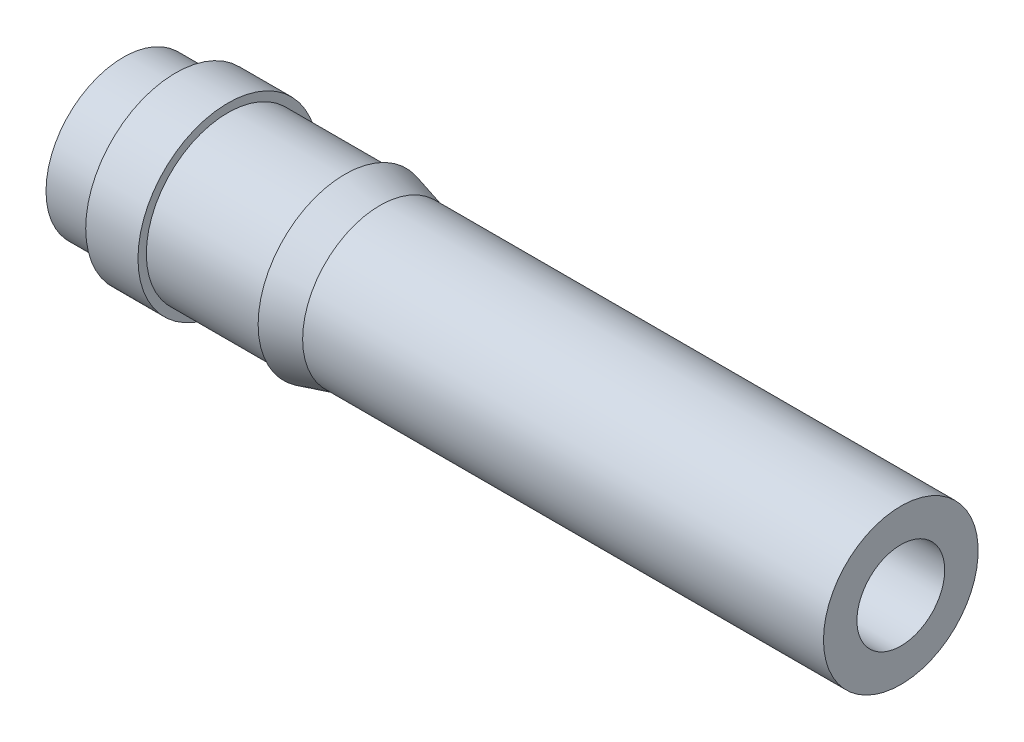
SolidWorks part; units mm, degrees
material "Brass Alloy 385"
ref_plane "Front Plane" through (0, 0, 0) normal (0, 0, 1) x (1, 0, 0)
ref_plane "Top Plane" through (0, 0, 0) normal (0, 1, 0) x (1, 0, 0)
ref_plane "Right Plane" through (0, 0, 0) normal (1, 0, 0) x (0, 0, -1)
sketch "Sketch1" plane through (0, 0, 0) normal (0, 0, 1) x (1, 0, 0)
  line L0 (0, 0) -> (0, 0.4699)
  line L1 (0.3175, 0.5461) -> (0.635, 0.5461)
  line L2 (0.635, 0.5461) -> (0.635, 0.4953)
  line L3 (0.635, 0.4953) -> (1.3462, 0.4953)
  line L4 (1.3462, 0.4953) -> (1.3462, 0.527)
  line L5 (1.3462, 0.527) -> (1.5595, 0.4699)
  line L6 (1.5595, 0.4699) -> (4.7244, 0.4699)
  line L7 (0.3175, 0.5461) -> (0.3175, 0.4699)
  line L8 (4.7244, 0.4699) -> (4.7244, 0)
  line L9 (0, 0) -> (4.7244, 0)
  line L10 (0, 0) -> (4.7244, 0) construction
  line L11 (0.3175, 0.4699) -> (0, 0.4699)
  line L12 (0, 0) -> (4.7244, 0) construction
revolve "RevolutionAngle1" add sketch "Sketch1" angle 360 about L10
hole_wizard "Hole1" positions "Sketch3" profile "Sketch2" legacy
sketch "Sketch3" plane through (0, 0, 0) normal (-1, 0, 0) x (0, 0, 1)
  point P0 (0, 0)
sketch "Sketch2" plane through (0, 0, 0) normal (0, 1, 0) x (0, 0, 1)
  line L0 (0, 0) -> (0, 4.1476)
  line L1 (0, 4.1476) -> (0.3505, 3.937)
  line L2 (0.3505, 3.937) -> (0.3505, 0)
  line L4 (0.3505, 0) -> (0, 0)
  line L6 (0, 4.1476) -> (-0.3505, 3.937) construction
  line L7 (0, -4.2442) -> (0, 117.3081) construction
  dimension "A1" = 0.701
  dimension "N" = 3.937
  dimension "Drill Angle" = 118
hole_wizard "Hole2" positions "Sketch5" profile "Sketch4" legacy end condition through all
sketch "Sketch5" plane through (4.7244, 0, 0) normal (1, 0, 0) x (0, 0, -1)
  point P0 (0, 0)
sketch "Sketch4" plane through (4.7244, 0, 0) normal (0, 1, 0) x (0, 0, -1)
  line L0 (0, 0) -> (0, 4.8846)
  line L1 (0, 4.8846) -> (0.2667, 4.7244)
  line L2 (0.2667, 4.7244) -> (0.2667, 0)
  line L4 (0.2667, 0) -> (0, 0)
  line L6 (0, 4.8846) -> (-0.2667, 4.7244) construction
  line L7 (0, -4.2442) -> (0, 117.3081) construction
  dimension "A2" = 0.5334
  dimension "Depth" = 4.7244
  dimension "Drill Angle" = 118
